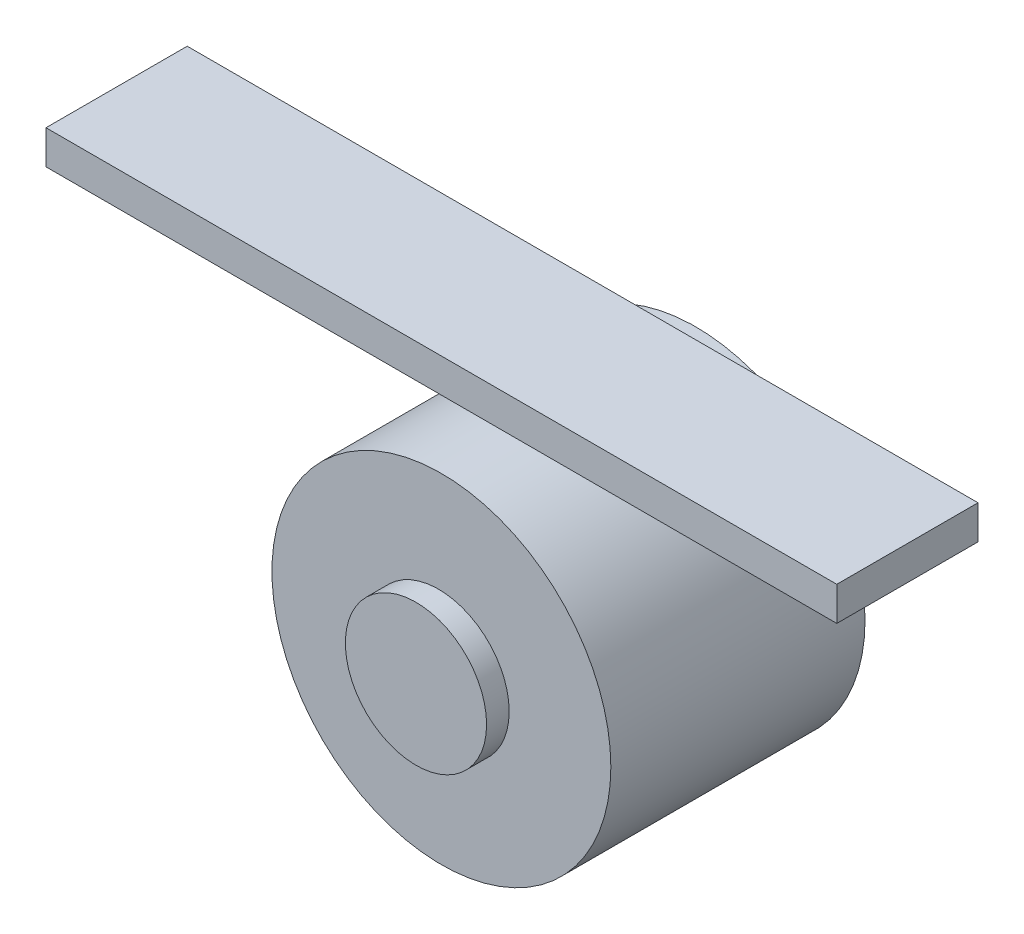
SolidWorks part; units mm, degrees
ref_plane "前视基准面" through (0, 0, 0) normal (0, 0, 1) x (1, 0, 0)
ref_plane "上视基准面" through (0, 0, 0) normal (0, 1, 0) x (1, 0, 0)
ref_plane "右视基准面" through (0, 0, 0) normal (1, 0, 0) x (0, 0, -1)
other "Configuration Table"
sketch "草图1" plane through (0, 0, 0) normal (0, 0, 1) x (1, 0, 0)
  circle A0 centre (0, 0) radius 6
extrude "active buzzer - dia 12 x 9 mm" add sketch "草图1" along normal blind 9 from offset 4.5 separate body
sketch "草图2" plane through (0, 0, 0) normal (0, 0, 1) x (1, 0, 0)
  circle A0 centre (0, 0) radius 2.5
extrude "sound outlet marker" add sketch "草图2" along normal blind 0.8 from offset 4.6 separate body
sketch "草图3" plane through (0, 0, 0) normal (0, 0, 1) x (1, 0, 0)
  line L1 (-14, 8.4) -> (14, 8.4)
  line L2 (-14, 8.4) -> (-14, 9.6)
  line L3 (-14, 9.6) -> (14, 9.6)
  line L4 (14, 8.4) -> (14, 9.6)
  line L5 (-14, 8.4) -> (14, 9.6) construction
  line L6 (-14, 9.6) -> (14, 8.4) construction
  point P0 (0, 9)
extrude "buzzer label plate - BUZZER" add sketch "草图3" along normal blind 5 from offset 0.5 separate body
